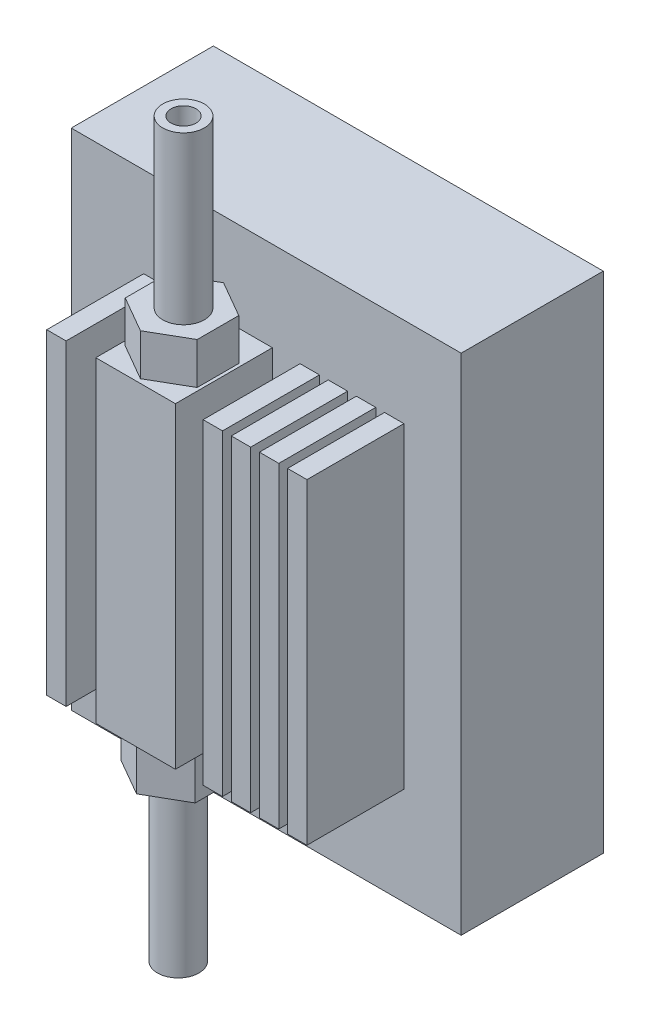
SolidWorks part; units mm, degrees
ref_plane "Front Plane" through (0, 0, 0) normal (0, 0, 1) x (1, 0, 0)
ref_plane "Top Plane" through (0, 0, 0) normal (0, 1, 0) x (1, 0, 0)
ref_plane "Right Plane" through (0, 0, 0) normal (1, 0, 0) x (0, 0, -1)
sketch "Sketch1" plane through (0, 0, 0) normal (0, 0, 1) x (1, 0, 0)
  line L1 (-770.8651, 173.48) -> (-742.7151, 173.48)
  line L2 (-770.8651, 173.48) -> (-770.8651, 137.08)
  line L3 (-770.8651, 137.08) -> (-742.7151, 137.08)
  line L4 (-742.7151, 173.48) -> (-742.7151, 137.08)
  dimension "D1" = 28.15
  dimension "D2" = 36.4
extrude "Boss-Extrude1" add sketch "Sketch1" along normal blind 10.26
sketch "Sketch2" plane through (0, 0, 10.26) normal (0, 0, 1) x (1, 0, 0)
  line L0 (-756.3446, 163.1648) -> (-754.3446, 163.1648)
  line L1 (-750.2806, 144.1469) -> (-750.2806, 167.0069)
  line L2 (-748.8806, 144.1469) -> (-748.8806, 167.0069)
  line L3 (-748.2486, 144.1469) -> (-748.2486, 167.0069)
  line L4 (-746.8486, 167.0069) -> (-748.2486, 167.0069)
  line L6 (-748.8806, 167.0069) -> (-750.2806, 167.0069)
  line L7 (-746.8486, 144.1469) -> (-748.2486, 144.1469)
  line L8 (-748.8806, 144.1469) -> (-750.2806, 144.1469)
  line L9 (-746.8486, 144.1469) -> (-746.8486, 167.0069)
  line L10 (-742.7151, 163.1648) -> (-746.7151, 163.1648)
  line L11 (-742.7151, 137.08) -> (-742.7151, 173.48) construction
  line L12 (-752.6275, 173.48) -> (-752.6275, 167.48)
  line L13 (-752.9446, 144.1469) -> (-754.3446, 144.1469)
  line L14 (-752.9446, 144.1469) -> (-752.9446, 167.0069)
  line L15 (-752.9446, 167.0069) -> (-754.3446, 167.0069)
  line L16 (-754.3446, 144.1469) -> (-754.3446, 167.0069)
  line L17 (-756.3446, 144.1469) -> (-762.0946, 144.1469)
  line L18 (-756.3446, 144.1469) -> (-756.3446, 167.0069)
  line L19 (-756.3446, 167.0069) -> (-762.0946, 167.0069)
  line L20 (-762.0946, 144.1469) -> (-762.0946, 167.0069)
  line L21 (-752.3126, 144.1469) -> (-752.3126, 167.0069)
  line L22 (-750.9126, 144.1469) -> (-750.9126, 167.0069)
  line L23 (-750.9126, 167.0069) -> (-752.3126, 167.0069)
  line L24 (-750.9126, 144.1469) -> (-752.3126, 144.1469)
  line L25 (-752.9446, 165.6802) -> (-752.3126, 165.6802)
  line L26 (-750.9126, 165.6802) -> (-750.2806, 165.6802)
  line L27 (-748.8806, 165.6802) -> (-748.2486, 165.6802)
  line L28 (-742.7151, 173.48) -> (-770.8651, 173.48) construction
  line L29 (-764.2363, 144.1258) -> (-765.6363, 144.1258)
  line L30 (-764.2363, 144.1258) -> (-764.2363, 166.9858)
  line L31 (-764.2363, 166.9858) -> (-765.6363, 166.9858)
  line L32 (-765.6363, 144.1258) -> (-765.6363, 166.9858)
  line L33 (-762.0946, 162.1338) -> (-764.0946, 162.1338)
  dimension "D2" = 2
  dimension "D3" = 2
  dimension "D4" = 5.75
  dimension "D5" = 4
  dimension "D6" = 6
  dimension "D7" = 0.632
  dimension "D8" = 2
  dimension "D9" = 22.86
  dimension "D10" = 22.86
  dimension "D11" = 22.86
  dimension "D12" = 2
extrude "Boss-Extrude5" add sketch "Sketch2" along normal blind 7 contours L20 L17 L18 L19 | L16 L13 L14 L15 | L8 L2 L6 L1 | L7 L9 L4 L3 | L21 L23 L22 L24 | L32 L31 L30 L29
sketch "Sketch4" plane through (0, 144.1469, 0) normal (0, -1, 0) x (1, 0, 0)
  line L1 (-759.2088, 11.0004) -> (-756.5241, 12.5504)
  line L2 (-756.5241, 12.5504) -> (-756.5241, 15.6504)
  line L3 (-756.5241, 15.6504) -> (-759.2088, 17.2004)
  line L4 (-759.2088, 17.2004) -> (-761.8935, 15.6504)
  line L5 (-761.8935, 15.6504) -> (-761.8935, 12.5504)
  line L6 (-761.8935, 12.5504) -> (-759.2088, 11.0004)
  circle A0 centre (-759.2088, 14.1004) radius 2.6847 construction
  dimension "D1" = 3.1
extrude "Boss-Extrude6" add sketch "Sketch4" along normal blind 3
sketch "Sketch5" plane through (0, 141.1469, 0) normal (0, -1, 0) x (1, 0, 0)
  circle A0 centre (-759.2554, 14.1478) radius 0.9
  circle A1 centre (-759.2554, 14.1478) radius 1.5
  dimension "D1" = 1.8
  dimension "D2" = 3
extrude "Boss-Extrude7" add sketch "Sketch5" along normal blind 12
sketch "Sketch6" plane through (0, 167.0069, 0) normal (0, 1, 0) x (1, 0, 0)
  line L1 (-759.1676, -16.9622) -> (-756.5695, -15.4622)
  line L2 (-756.5695, -15.4622) -> (-756.5695, -12.4622)
  line L3 (-756.5695, -12.4622) -> (-759.1676, -10.9622)
  line L4 (-759.1676, -10.9622) -> (-761.7657, -12.4622)
  line L5 (-761.7657, -12.4622) -> (-761.7657, -15.4622)
  line L6 (-761.7657, -15.4622) -> (-759.1676, -16.9622)
  circle A0 centre (-759.1676, -13.9622) radius 2.5981 construction
  dimension "D1" = 3
sketch "Sketch7" plane through (0, 167.0069, 0) normal (0, 1, 0) x (1, 0, 0)
extrude "Boss-Extrude8" add sketch "Sketch6" along normal blind 3
sketch "Sketch8" plane through (0, 170.0069, 0) normal (0, 1, 0) x (1, 0, 0)
  circle A0 centre (-759.0422, -13.9763) radius 0.9
  circle A1 centre (-759.0422, -13.9763) radius 1.5
  dimension "D1" = 1.8
  dimension "D2" = 3
extrude "Boss-Extrude9" add sketch "Sketch8" along normal blind 12
